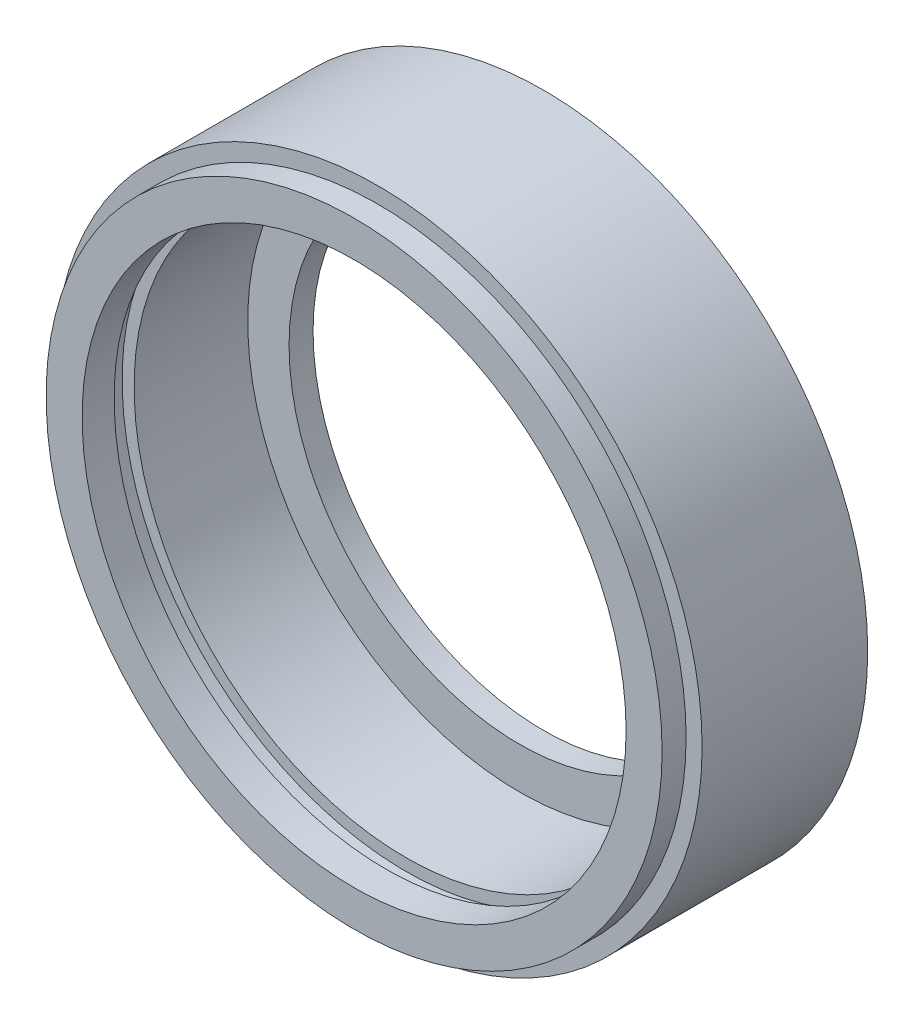
SolidWorks part; units mm, degrees
material "СТ3КП"
ref_plane "Спереди" through (0, 0, 0) normal (0, 0, 1) x (1, 0, 0)
ref_plane "Сверху" through (0, 0, 0) normal (0, 1, 0) x (1, 0, 0)
ref_plane "Справа" through (0, 0, 0) normal (1, 0, 0) x (0, 0, -1)
sketch "Эскиз1" plane through (0, 0, 0) normal (1, 0, 0) x (0, 0, -1)
  line L0 (0, 0) -> (0, 40.5) construction
  line L1 (-23.7, 0) -> (-23.7, 150) construction
  line L2 (-23.7, 38.5) -> (-20.7, 38.5) construction
  line L3 (-20.7, 38.5) -> (-20.7, 40.5) construction
  line L4 (-23.7, 40.5) -> (0, 40.5) construction
  line L5 (0, 28.8333) -> (0, 40.5)
  line L6 (-23.7, 34) -> (-23.7, 38.5)
  line L7 (-23.7, 38.5) -> (-20.7, 38.5)
  line L8 (-20.7, 38.5) -> (-20.7, 40.5)
  line L9 (-20.7, 40.5) -> (0, 40.5)
  line L10 (-23.7, 34) -> (-19.7, 34)
  line L11 (-3, 34) -> (-3, 28.8333)
  line L12 (-3, 28.8333) -> (0, 28.8333)
  line L13 (-4.5, 34) -> (-16.5, 34) construction
  line L14 (-3, -32.5) -> (-3, 32.5) construction
  line L15 (-19.7, 35.5) -> (-19.7, -34.3561) construction
  line L16 (-19.7, 35.5) -> (-19.7, 34)
  line L17 (-19.7, 35.5) -> (-17.2, 35.5)
  line L18 (-17.2, 35.5) -> (-17.2, 34)
  line L19 (-17.2, 34) -> (-3, 34)
  line L20 (-3, 28.8333) -> (-5.5, 28.8333) construction
  line L21 (-1010.5, 0) -> (48989.5, 0) construction
  dimension "D1" = 2.5
revolve "Повернуть1" add sketch "Эскиз1" angle 360 about L21
